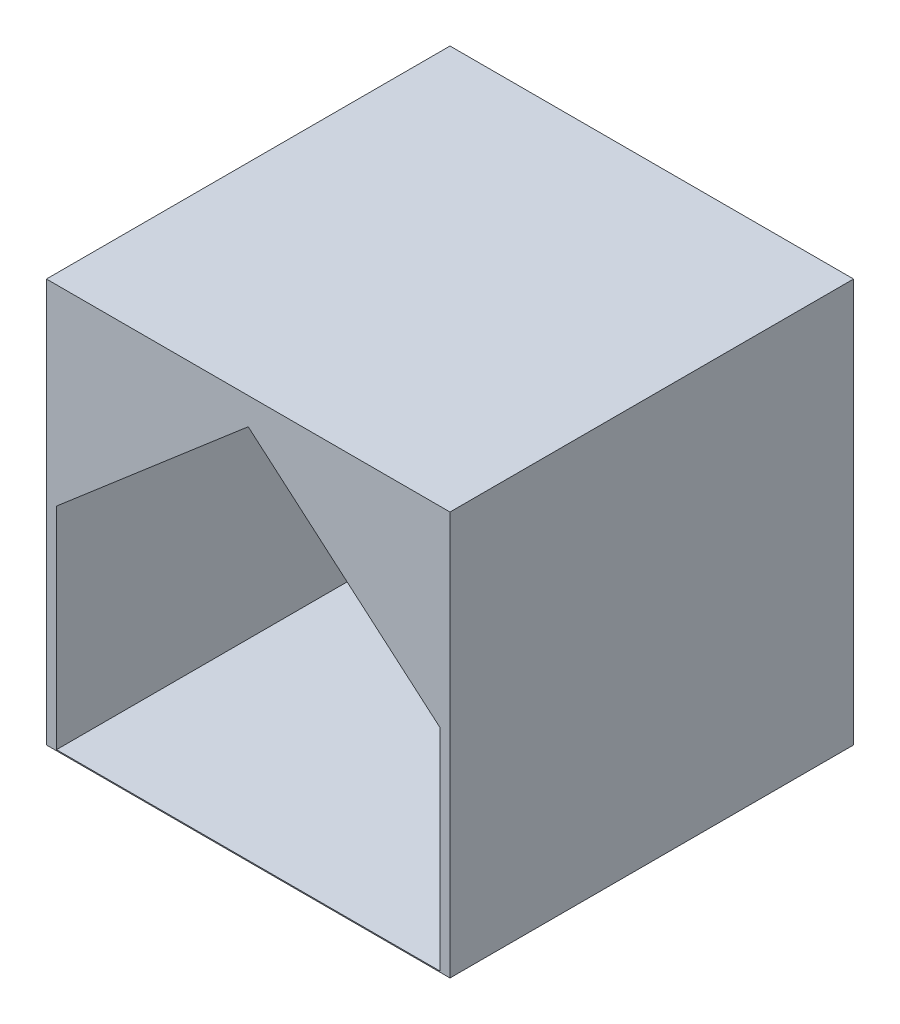
SolidWorks part; units mm, degrees
ref_plane "Front Plane" through (0, 0, 0) normal (0, 0, 1) x (1, 0, 0)
ref_plane "Top Plane" through (0, 0, 0) normal (0, 1, 0) x (1, 0, 0)
ref_plane "Right Plane" through (0, 0, 0) normal (1, 0, 0) x (0, 0, -1)
sketch "Sketch1" plane through (0, 0, 0) normal (0, 0, 1) x (1, 0, 0)
  line L0 (-1599.1508, 0) -> (1757.5573, 0) construction
  line L1 (0, 899.5223) -> (0, -922.1518) construction
  line L3 (1000, -1000) -> (-1000, -1000)
  line L4 (1000, -1000) -> (1000, 1000)
  line L5 (1000, 1000) -> (-1000, 1000)
  line L6 (-1000, -1000) -> (-1000, 1000)
  line L7 (1000, -1000) -> (-1000, 1000) construction
  line L8 (1000, 1000) -> (-1000, -1000) construction
  point P5 (0, 0)
  dimension "D1" = 2000
  dimension "D2" = 2000
extrude "Boss-Extrude1" add sketch "Sketch1" along normal blind 2000
sketch "Sketch2" plane through (0, 0, 2000) normal (0, 0, 1) x (1, 0, 0)
  line L0 (-950, -995) -> (-950, 50.5007)
  line L2 (-1000, -1000) -> (1000, -1000) construction
  line L4 (-950, 50.5007) -> (0, 865.901)
  line L5 (0, 865.901) -> (950, 50.5007)
  line L6 (950, 50.5007) -> (950, -995)
  line L7 (0, 135.3461) -> (0, -1116.6034) construction
  line L8 (-1000, 1000) -> (-1000, -1000) construction
  line L9 (-950, -995) -> (950, -995)
  dimension "D1" = 50
  dimension "D2" = 1900
  dimension "D3" = 5
extrude "Cut-Extrude4" cut sketch "Sketch2" against normal blind 1995 and the other way through all
sketch "Sketch3" plane through (-427.9461, 498.588, 0) normal (0.6513, -0.7588, 0) x (0.7588, 0.6513, 0)
  line L0 (-62.0096, 2000) -> (-62.0096, 0) construction
  line L1 (-687.9844, 2000) -> (563.9651, 2000) construction
  line L2 (-687.9844, 0) -> (563.9651, 0) construction
  line L3 (-687.9844, 1002.5) -> (563.9651, 1002.5) construction
  line L4 (-687.9844, 5) -> (-687.9844, 2000) construction
  line L5 (563.9651, 5) -> (563.9651, 2000) construction
  line L6 (-687.9844, 1500) -> (563.9651, 1500) construction
  line L7 (-687.9844, 502.5) -> (563.9651, 502.5) construction
  circle A0 centre (-62.0096, 1500) radius 100
  circle A1 centre (-62.0096, 1000) radius 100
  circle A2 centre (-62.0096, 502.5) radius 100
  dimension "D1" = 500
  dimension "D2" = 500
sketch "Sketch6" plane through (427.9461, 498.588, 0) normal (-0.6513, -0.7588, 0) x (0.7588, -0.6513, 0)
  line L0 (-563.9651, 1500) -> (687.9844, 1500) construction
  line L1 (687.9844, 5) -> (687.9844, 2000) construction
  line L2 (-563.9651, 1002.5) -> (687.9844, 1002.5) construction
  line L3 (-563.9651, 502.5) -> (687.9844, 502.5) construction
  line L4 (62.0096, 2000) -> (62.0096, 0) construction
  line L5 (-563.9651, 2000) -> (687.9844, 2000) construction
  line L6 (-563.9651, 0) -> (687.9844, 0) construction
  circle A0 centre (62.0096, 1500) radius 100
  circle A1 centre (62.0096, 1002.5) radius 100
  circle A2 centre (62.0096, 502.5) radius 100
extrude "Cut-Extrude5" cut sketch "Sketch6" against normal blind 20
extrude "Cut-Extrude6" cut sketch "Sketch3" against normal blind 20
